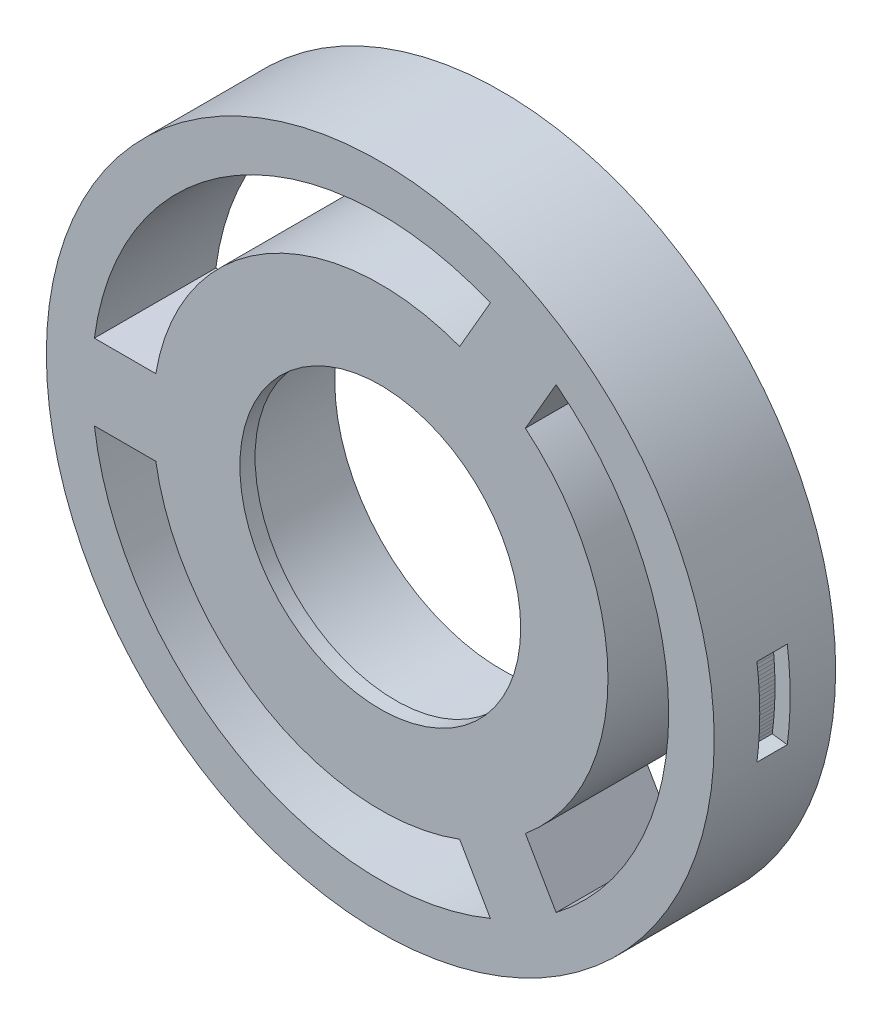
SolidWorks part; units mm, degrees
ref_plane "Front Plane" through (0, 0, 0) normal (0, 0, 1) x (1, 0, 0)
ref_plane "Top Plane" through (0, 0, 0) normal (0, 1, 0) x (1, 0, 0)
ref_plane "Right Plane" through (0, 0, 0) normal (1, 0, 0) x (0, 0, -1)
sketch "Sketch1" plane through (0, 0, 0) normal (0, 0, 1) x (1, 0, 0)
  circle A0 centre (0, 0) radius 22
  circle A1 centre (0, 0) radius 19
extrude "Outer_ring" add sketch "Sketch1" along normal blind 8
sketch "Sketch2" plane through (0, 0, 0) normal (0, 0, 1) x (1, 0, 0)
  circle A0 centre (0, 0) radius 15
  circle A1 centre (0, 0) radius 9.25
extrude "Hub" add sketch "Sketch2" along normal blind 8
sketch "Sketch3" plane through (0, 0, 0) normal (0, 0, 1) x (1, 0, 0)
  line L0 (9.1651, 10.8744) -> (12.1651, 16.0705)
  line L1 (12.1651, 16.0705) -> (7.8349, 18.5705)
  line L2 (7.8349, 18.5705) -> (4.8349, 13.3744)
  line L3 (4.8349, 13.3744) -> (9.1651, 10.8744)
  line L4 (-14, 2.5) -> (-20, 2.5)
  line L5 (-20, 2.5) -> (-20, -2.5)
  line L6 (-20, -2.5) -> (-14, -2.5)
  line L7 (-14, -2.5) -> (-14, 2.5)
  line L8 (4.8349, -13.3744) -> (7.8349, -18.5705)
  line L9 (7.8349, -18.5705) -> (12.1651, -16.0705)
  line L10 (12.1651, -16.0705) -> (9.1651, -10.8744)
  line L11 (9.1651, -10.8744) -> (4.8349, -13.3744)
extrude "Spokes" add sketch "Sketch3" along normal blind 8
sketch "Sketch4" plane through (0, 0, 0) normal (0, 0, 1) x (1, 0, 0)
  circle A0 centre (0, 0) radius 11
extrude "Bearing_seat" cut sketch "Sketch4" along normal blind 7
ref_plane "Plane_z3" through (0, 0, 3) normal (0, 0, 1) x (1, 0, 0)
sketch "Sketch5" plane through (0, 0, 3) normal (0, 0, 1) x (1, 0, 0)
  line L0 (20.8203, -2.7411) -> (20.849, -2.5138)
  line L1 (20.849, -2.5138) -> (20.8752, -2.2862)
  line L2 (20.8752, -2.2862) -> (20.8989, -2.0584)
  line L3 (20.8989, -2.0584) -> (20.9201, -1.8303)
  line L4 (20.9201, -1.8303) -> (20.9388, -1.602)
  line L5 (20.9388, -1.602) -> (20.955, -1.3735)
  line L6 (20.955, -1.3735) -> (20.9688, -1.1448)
  line L7 (20.9688, -1.1448) -> (20.98, -0.916)
  line L8 (20.98, -0.916) -> (20.9888, -0.6871)
  line L9 (20.9888, -0.6871) -> (20.995, -0.4581)
  line L10 (20.995, -0.4581) -> (20.9988, -0.2291)
  line L11 (20.9988, -0.2291) -> (21, 0)
  line L12 (21, 0) -> (20.9988, 0.2291)
  line L13 (20.9988, 0.2291) -> (20.995, 0.4581)
  line L14 (20.995, 0.4581) -> (20.9888, 0.6871)
  line L15 (20.9888, 0.6871) -> (20.98, 0.916)
  line L16 (20.98, 0.916) -> (20.9688, 1.1448)
  line L17 (20.9688, 1.1448) -> (20.955, 1.3735)
  line L18 (20.955, 1.3735) -> (20.9388, 1.602)
  line L19 (20.9388, 1.602) -> (20.9201, 1.8303)
  line L20 (20.9201, 1.8303) -> (20.8989, 2.0584)
  line L21 (20.8989, 2.0584) -> (20.8752, 2.2862)
  line L22 (20.8752, 2.2862) -> (20.849, 2.5138)
  line L23 (20.849, 2.5138) -> (20.8203, 2.7411)
  line L24 (20.8203, 2.7411) -> (23.299, 3.0674)
  line L25 (23.299, 3.0674) -> (23.299, -3.0674)
  line L26 (23.299, -3.0674) -> (20.8203, -2.7411)
extrude "Screw_groove" cut sketch "Sketch5" along normal blind 2
